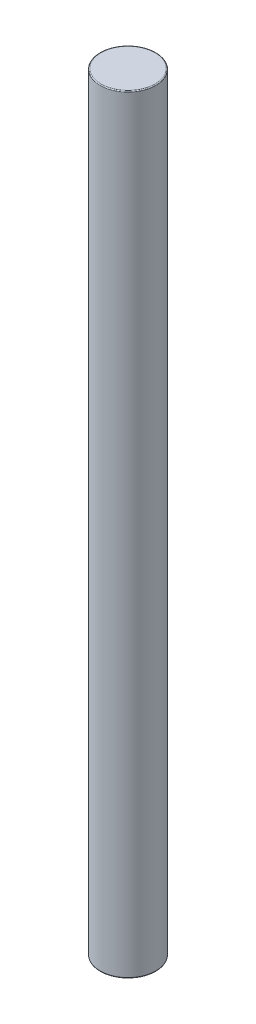
SolidWorks part; units mm, degrees
material "201 Annealed Stainless Steel (SS)"
ref_plane "Plan de face" through (0, 0, 0) normal (0, 0, 1) x (1, 0, 0)
ref_plane "Plan de dessus" through (0, 0, 0) normal (0, 1, 0) x (1, 0, 0)
ref_plane "Plan de droite" through (0, 0, 0) normal (1, 0, 0) x (0, 0, -1)
sketch "Sketch1" plane through (0, 0, 0) normal (0, 1, 0) x (1, 0, 0)
  circle A0 centre (0, 0) radius 6
  dimension "D1" = 12
extrude "Boss-Extrude1" add sketch "Sketch1" along normal mid plane 165
fillet "Fillet1" radius 0.2 2 edges at (0, -82.5, 6) (0, 82.5, 6)
